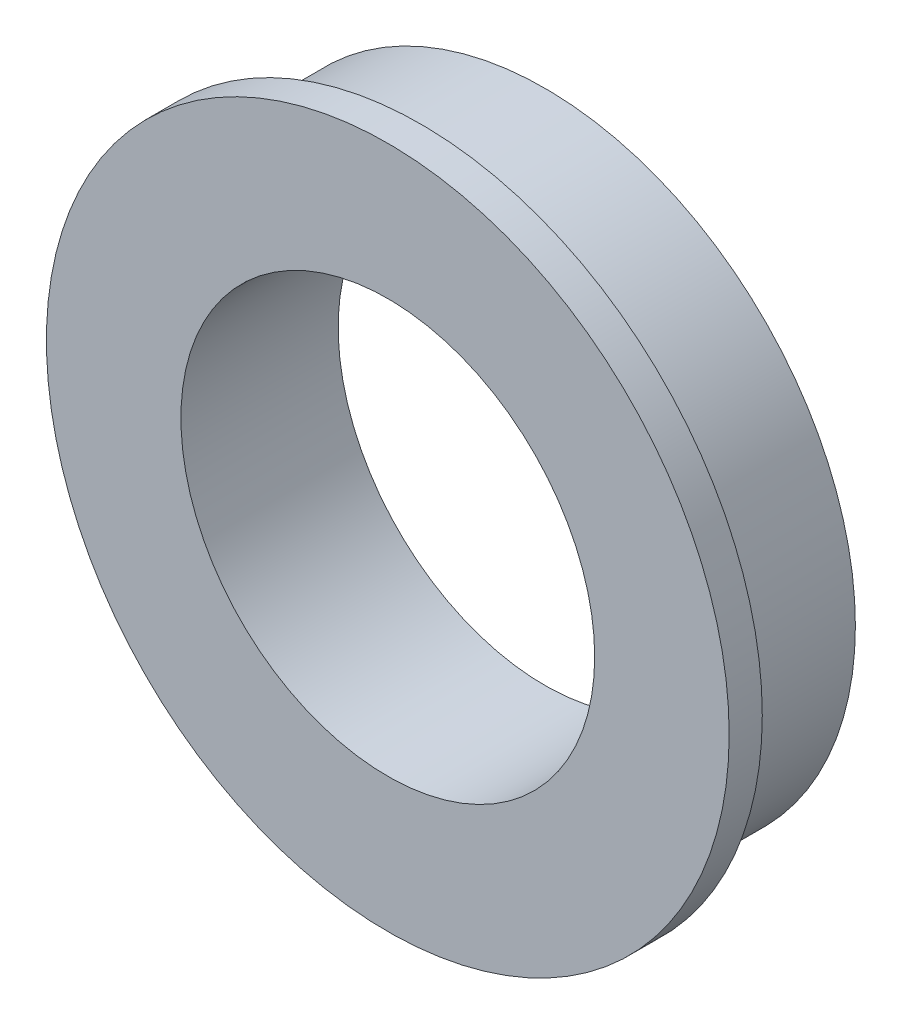
SolidWorks part; units mm, degrees
ref_plane "Front" through (0, 0, 0) normal (0, 0, 1) x (1, 0, 0)
ref_plane "Top" through (0, 0, 0) normal (0, 1, 0) x (1, 0, 0)
ref_plane "Right" through (0, 0, 0) normal (1, 0, 0) x (0, 0, -1)
sketch "Sketch1" plane through (0, 0, 0) normal (0, 0, 1) x (1, 0, 0)
  circle A0 centre (0, 0) radius 5
  circle A1 centre (0, 0) radius 7.5
  dimension "D1" = 10
  dimension "D2" = 15
extrude "Boss-Extrude1" add sketch "Sketch1" along normal blind 3
sketch "Sketch2" plane through (0, 0, 3) normal (0, 0, 1) x (1, 0, 0)
  circle A0 centre (0, 0) radius 8.25
  circle A1 centre (0, 0) radius 5
  dimension "D1" = 16.5
extrude "Boss-Extrude2" add sketch "Sketch2" along normal blind 0.8
